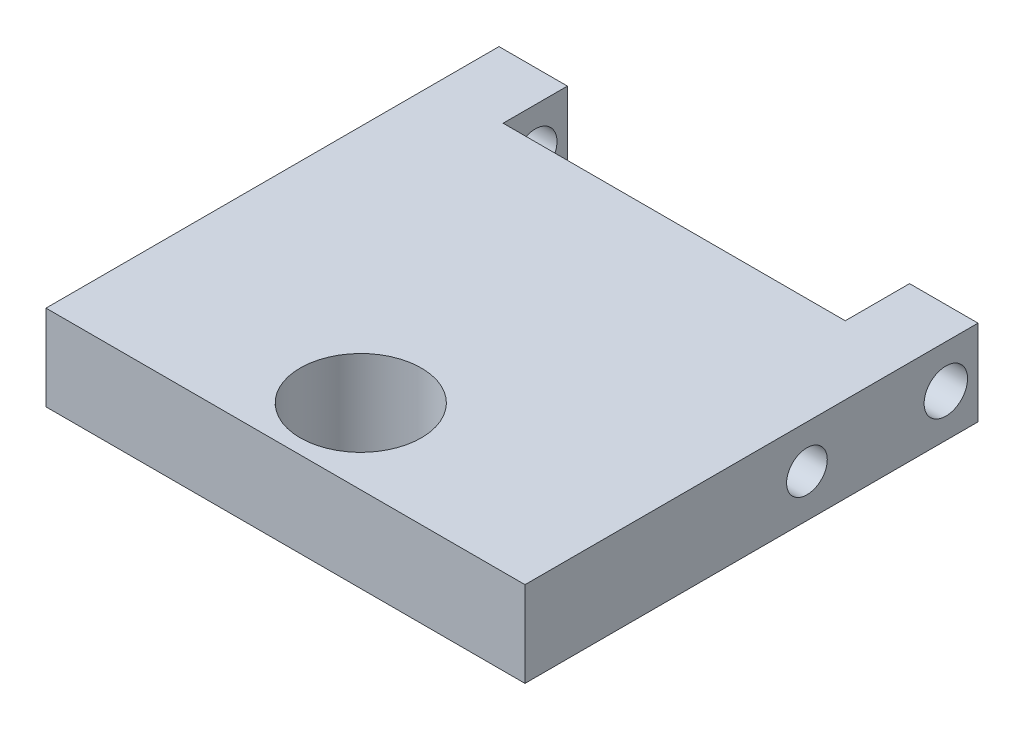
SolidWorks part; units mm, degrees
material "6061 Alloy"
ref_plane "Front Plane" through (0, 0, 0) normal (0, 0, 1) x (1, 0, 0)
ref_plane "Top Plane" through (0, 0, 0) normal (0, 1, 0) x (1, 0, 0)
ref_plane "Right Plane" through (0, 0, 0) normal (1, 0, 0) x (0, 0, -1)
sketch "Sketch1" plane through (0, 0, 0) normal (0, 1, 0) x (1, 0, 0)
  line L1 (-8.89, -8.4074) -> (8.89, -8.4074)
  line L2 (-8.89, -8.4074) -> (-8.89, 8.4074)
  line L3 (-8.89, 8.4074) -> (8.89, 8.4074)
  line L4 (8.89, -8.4074) -> (8.89, 8.4074)
  line L5 (-8.89, -8.4074) -> (8.89, 8.4074) construction
  line L6 (-8.89, 8.4074) -> (8.89, -8.4074) construction
  point P0 (0, 0)
  dimension "D1" = 17.78
  dimension "D2" = 16.8148
extrude "Boss-Extrude1" add sketch "Sketch1" along normal blind 3.175
sketch "Sketch2" plane through (0, 3.175, 0) normal (0, 1, 0) x (1, 0, 0)
  line L0 (8.89, 8.4074) -> (-8.89, 8.4074) construction
  line L1 (-6.35, 10.795) -> (6.35, 10.795)
  line L2 (-6.35, 10.795) -> (-6.35, 6.0198)
  line L3 (-6.35, 6.0198) -> (6.35, 6.0198)
  line L4 (6.35, 10.795) -> (6.35, 6.0198)
  line L5 (-6.35, 10.795) -> (6.35, 6.0198) construction
  line L6 (-6.35, 6.0198) -> (6.35, 10.795) construction
  line L7 (-8.89, 8.4074) -> (-8.89, -8.4074) construction
  point P0 (0, 8.4074)
  dimension "D1" = 2.3876
  dimension "D2" = 2.54
extrude "Cut-Extrude1" cut sketch "Sketch2" against normal through all contours L1 L4 L3 L2
hole_wizard "#8 Clearance Hole1" positions "Sketch6" profile "Sketch7" hole size "#8" standard "ANSI Inch" end condition through all
sketch "Sketch6" plane through (0, 3.175, 0) normal (0, 1, 0) x (1, 0, 0)
  line L2 (8.89, -8.4074) -> (8.89, 8.4074) construction
  line L3 (-8.89, -8.4074) -> (8.89, -8.4074) construction
  point P0 (0, -5.6134)
  dimension "D1" = 2.794
  dimension "D2" = 8.89
sketch "Sketch7" plane through (0, 3.175, 5.6134) normal (1, 0, 0) x (0, 0, 1)
  line L0 (0, 0) -> (0, 3.175)
  line L1 (0, 3.175) -> (2.2479, 3.175)
  line L2 (2.2479, 3.175) -> (2.2479, 0)
  line L5 (2.2479, 0) -> (0, 0)
  line L11 (0, -6.35) -> (0, 107.95) construction
  dimension "Thru Hole Dia." = 4.4958
  dimension "Thru Hole Depth" = 3.175
hole_wizard "#0 Clearance Hole1" positions "Sketch10" profile "Sketch11" hole size "#0" standard "ANSI Inch" end condition through all
sketch "Sketch10" plane through (8.89, 0, 0) normal (1, 0, 0) x (0, 0, -1)
  line L0 (-8.4074, 3.175) -> (8.4074, 3.175) construction
  line L1 (8.4074, 3.175) -> (8.4074, 0) construction
  point P0 (7.2136, 1.5875)
  dimension "D1" = 1.5875
  dimension "D2" = 1.1938
sketch "Sketch11" plane through (8.89, 1.5875, -7.2136) normal (0, 1, 0) x (0, 0, -1)
  line L0 (0, 0) -> (0, 17.78)
  line L1 (0, 17.78) -> (0.8064, 17.78)
  line L2 (0.8064, 17.78) -> (0.8064, 0)
  line L5 (0.8064, 0) -> (0, 0)
  line L11 (0, -6.35) -> (0, 107.95) construction
  dimension "Thru Hole Dia." = 1.6129
  dimension "Thru Hole Depth" = 17.78
hole_wizard "#1-72 Tapped Hole1" positions "Sketch14" profile "Sketch15" tap size "#1-72" standard "ANSI Inch" end condition through all
sketch "Sketch14" plane through (8.89, 0, 0) normal (1, 0, 0) x (0, 0, -1)
  line L1 (-8.4074, 3.175) -> (8.4074, 3.175) construction
  line L2 (8.4074, 3.175) -> (8.4074, 0) construction
  point P0 (2.0574, 1.5875)
  dimension "D1" = 1.5875
  dimension "D2" = 6.35
cosmetic thread "Hole Thread1" parameters "D2"=1.8542
sketch "Sketch15" plane through (8.89, 1.5875, -2.0574) normal (0, 1, 0) x (0, 0, -1)
  line L0 (0, 0) -> (0, 17.78)
  line L1 (0, 17.78) -> (0.7556, 17.78)
  line L2 (0.7556, 17.78) -> (0.7556, 0)
  line L5 (0.7556, 0) -> (0, 0)
  line L11 (0, -6.35) -> (0, 107.95) construction
  dimension "Thru Tap Drill Dia." = 1.5113
  dimension "Thru Tap Drill Depth" = 17.78
sketch "Sketch16" plane through (0, 3.175, 0) normal (0, 1, 0) x (1, 0, 0)
  line L0 (-6.35, 8.4074) -> (-8.89, 8.4074) construction
  line L1 (2.54, 3.6449) -> (-13.2131, 3.6449)
  line L2 (2.54, 3.6449) -> (2.54, -8.4074)
  line L3 (2.54, -8.4074) -> (-13.2131, -8.4074)
  line L4 (-13.2131, 3.6449) -> (-13.2131, -8.4074)
  line L5 (-8.89, 8.4074) -> (-8.89, -8.4074) construction
  line L6 (-8.89, -8.4074) -> (8.89, -8.4074) construction
  dimension "D1" = 4.7625
  dimension "D2" = 11.43
  dimension "D3" = 0
extrude "Cut-Extrude2" [suppressed] cut sketch "Sketch16" against normal through all
